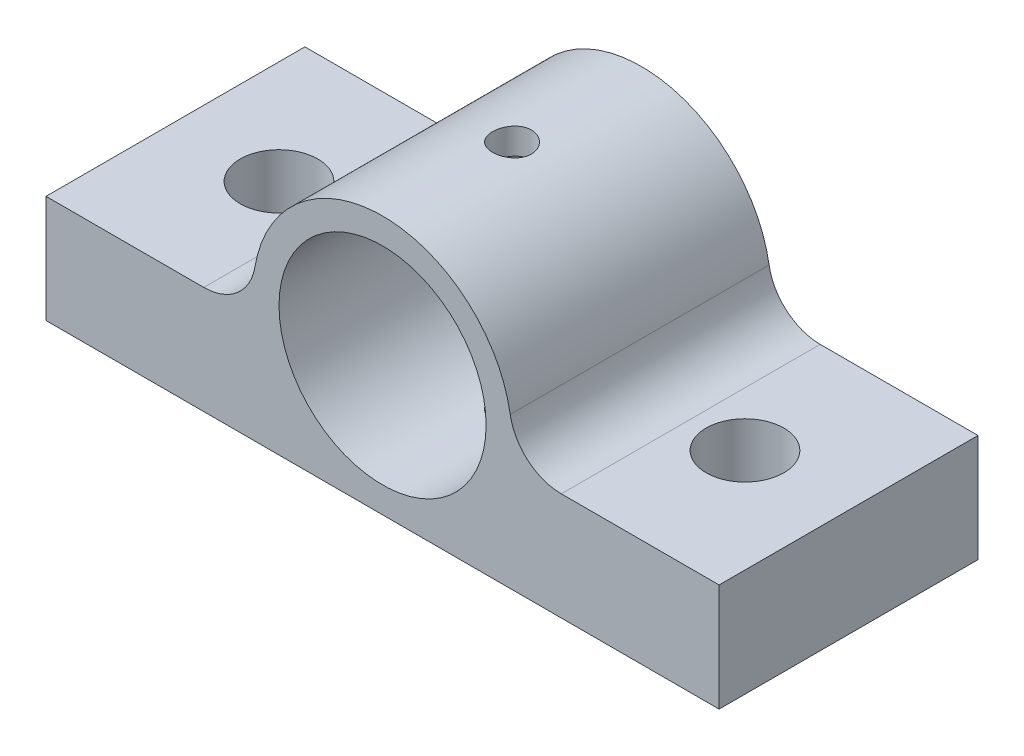
SolidWorks part; units mm, degrees
ref_plane "Front Plane" through (0, 0, 0) normal (0, 0, 1) x (1, 0, 0)
ref_plane "Top Plane" through (0, 0, 0) normal (0, 1, 0) x (1, 0, 0)
ref_plane "Right Plane" through (0, 0, 0) normal (1, 0, 0) x (0, 0, -1)
sketch "Sketch1" plane through (0, 0, 0) normal (0, 0, 1) x (1, 0, 0)
  line L0 (0, 0) -> (0, 77.4643) construction
  line L1 (0, 0) -> (-13, 0)
  line L2 (0, 0) -> (13, 0)
  line L3 (-13, 0) -> (-13, 4.155)
  line L4 (-13, 4.155) -> (-6.9041, 4.155)
  line L5 (13, 4.155) -> (13, 0)
  line L6 (0, 0) -> (0, 5)
  line L7 (6.9041, 4.155) -> (13, 4.155)
  arc A0 (4.9315, 5.825) -> (-4.9315, 5.825) centre (0, 5) ccw
  circle A1 centre (0, 5) radius 3
  circle A2 centre (0, 5) radius 4
  arc A3 (-4.9315, 5.825) -> (-6.9041, 4.155) centre (-6.9041, 6.155) cw
  arc A4 (6.9041, 4.155) -> (4.9315, 5.825) centre (6.9041, 6.155) cw
  point P16 (4.9281, 4.155)
  dimension "D1" = 2
  dimension "D2" = 2
extrude "Boss-Extrude1" add sketch "Sketch1" along normal blind 10 contours L0 A2 L6 L2 L5 L7 A4 A0 | A2 L0 A0 A3 L4 L3 L1 L6
sketch "Sketch2" plane through (0, 4.155, 0) normal (0, 1, 0) x (1, 0, 0)
  line L0 (0, -5) -> (9, -5)
  line L2 (0, -5) -> (-9, -5)
  circle A0 centre (-9, -5) radius 1.5
  circle A1 centre (9, -5) radius 1.5
  dimension "D1" = 9
extrude "Cut-Extrude1" cut sketch "Sketch2" against normal blind 10
sketch "Sketch3" plane through (0, 4.155, 0) normal (0, 1, 0) x (1, 0, 0)
  circle A0 centre (0, -5) radius 0.75
extrude "Cut-Extrude2" cut sketch "Sketch3" against normal through all both and the other way through all
